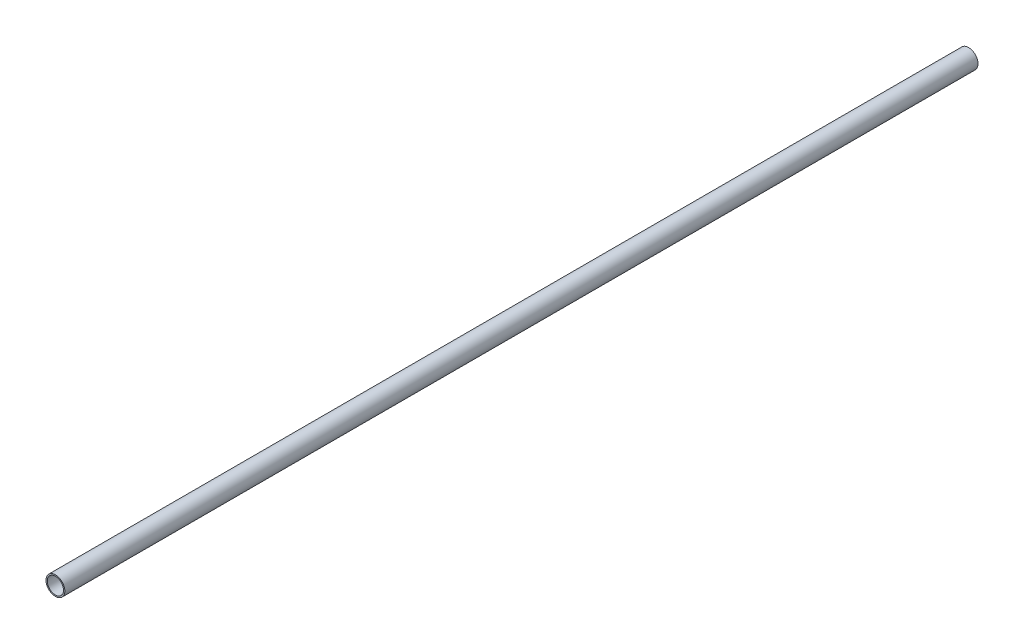
SolidWorks part; units mm, degrees
material "Thornel Mat VMA"
ref_plane "Front Plane" through (0, 0, 0) normal (0, 0, 1) x (1, 0, 0)
ref_plane "Top Plane" through (0, 0, 0) normal (0, 1, 0) x (1, 0, 0)
ref_plane "Right Plane" through (0, 0, 0) normal (1, 0, 0) x (0, 0, -1)
sketch "Sketch1" plane through (0, 0, 0) normal (0, 0, 1) x (1, 0, 0)
  circle A0 centre (0, 0) radius 7.25
  circle A1 centre (0, 0) radius 6.25
  dimension "D1" = 14.5
  dimension "D2" = 1
extrude "Boss-Extrude1" add sketch "Sketch1" along normal blind 703
equation "\"D1@Boss-Extrude1\"=703"
